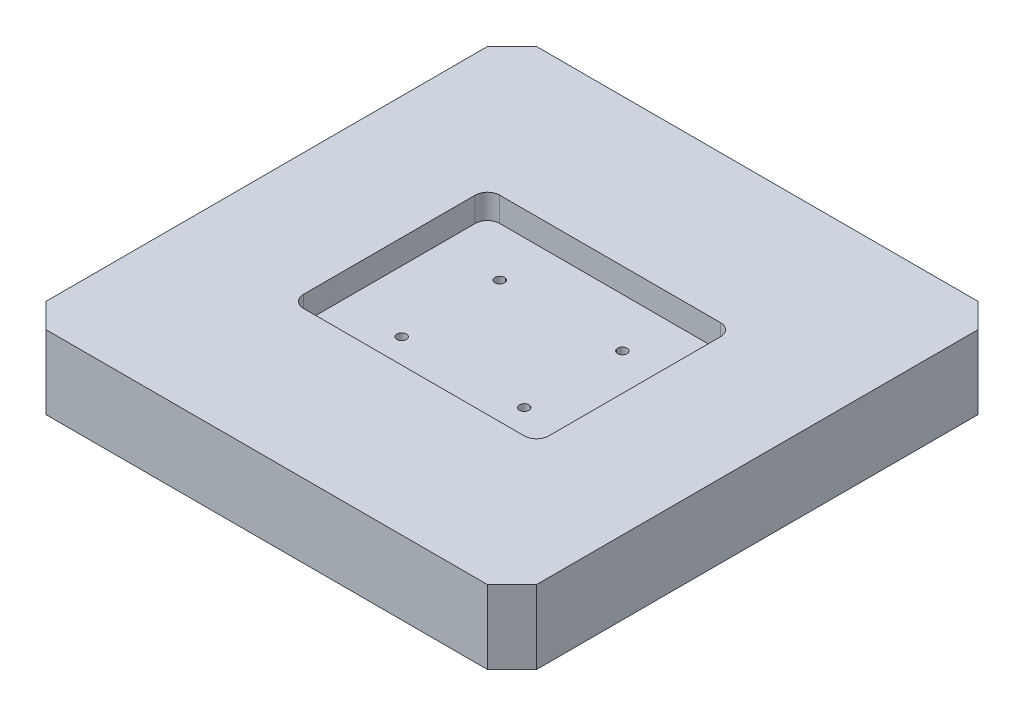
SolidWorks part; units mm, degrees
ref_plane "Front Plane" through (0, 0, 0) normal (0, 0, 1) x (1, 0, 0)
ref_plane "Top Plane" through (0, 0, 0) normal (0, 1, 0) x (1, 0, 0)
ref_plane "Right Plane" through (0, 0, 0) normal (1, 0, 0) x (0, 0, -1)
sketch "Sketch1" plane through (0, 0, 0) normal (0, 1, 0) x (1, 0, 0)
  line L1 (0, 0) -> (254, 0)
  line L2 (0, 0) -> (0, 254)
  line L3 (0, 254) -> (254, 254)
  line L4 (254, 0) -> (254, 254)
  dimension "D1" = 254
  dimension "D2" = 254
extrude "Boss-Extrude1" add sketch "Sketch1" along normal blind 38.1 contours L2 L1 L4 L3
sketch "Sketch2" plane through (0, 38.1, 0) normal (0, 1, 0) x (1, 0, 0)
  line L0 (0, 127) -> (254, 127) construction
  line L1 (0, 0) -> (0, 254) construction
  line L2 (254, 0) -> (254, 254) construction
  line L3 (127, 254) -> (127, 0) construction
  line L4 (0, 254) -> (254, 254) construction
  line L5 (0, 0) -> (254, 0) construction
  line L7 (69.85, 76.2) -> (184.15, 76.2)
  line L8 (63.5, 82.55) -> (63.5, 171.45)
  line L9 (69.85, 177.8) -> (184.15, 177.8)
  line L10 (190.5, 82.55) -> (190.5, 171.45)
  line L11 (63.5, 76.2) -> (190.5, 177.8) construction
  line L12 (63.5, 177.8) -> (190.5, 76.2) construction
  arc A0 (184.15, 177.8) -> (190.5, 171.45) centre (184.15, 171.45) cw
  arc A1 (184.15, 76.2) -> (190.5, 82.55) centre (184.15, 82.55) ccw
  arc A2 (69.85, 76.2) -> (63.5, 82.55) centre (69.85, 82.55) cw
  arc A3 (63.5, 171.45) -> (69.85, 177.8) centre (69.85, 171.45) cw
  point P12 (127, 127)
  dimension "D3" = 6.35
  dimension "D1" = 127
  dimension "D2" = 101.6
extrude "Cut-Extrude1" cut sketch "Sketch2" against normal blind 12.7 contours L8 A3 L9 A0 L10 A1 L7 A2
sketch "Sketch4" plane through (0, 25.4, 0) normal (0, 1, 0) x (1, 0, 0)
  line L0 (63.5, 127) -> (190.5, 127) construction
  line L3 (127, 177.8) -> (127, 76.2) construction
  line L6 (63.5, 82.55) -> (63.5, 171.45) construction
  line L7 (95.25, 101.6) -> (158.75, 101.6) construction
  line L8 (95.25, 101.6) -> (95.25, 152.4) construction
  line L9 (95.25, 152.4) -> (158.75, 152.4) construction
  line L10 (158.75, 101.6) -> (158.75, 152.4) construction
  line L11 (95.25, 101.6) -> (158.75, 152.4) construction
  line L12 (95.25, 152.4) -> (158.75, 101.6) construction
  line L13 (69.85, 177.8) -> (184.15, 177.8) construction
  line L14 (190.5, 82.55) -> (190.5, 171.45) construction
  line L15 (69.85, 76.2) -> (184.15, 76.2) construction
  circle A0 centre (95.25, 152.4) radius 2.4638
  circle A1 centre (158.75, 152.4) radius 2.4638
  circle A2 centre (158.75, 101.6) radius 2.4638
  circle A3 centre (95.25, 101.6) radius 2.4638
  point P3 (127, 127)
  point P8 (127, 127)
  point P29 (127, 127)
  dimension "D5" = 4.9276
  dimension "D1" = 50.8
  dimension "D2" = 63.5
extrude "Cut-Extrude2" cut sketch "Sketch4" against normal through all both and the other way through all
chamfer "Chamfer1" distance 12.7 angle 45 4 edges at (254, 19.05, -254) (254, 19.05, 0) (0, 19.05, 0) (0, 19.05, -254)
